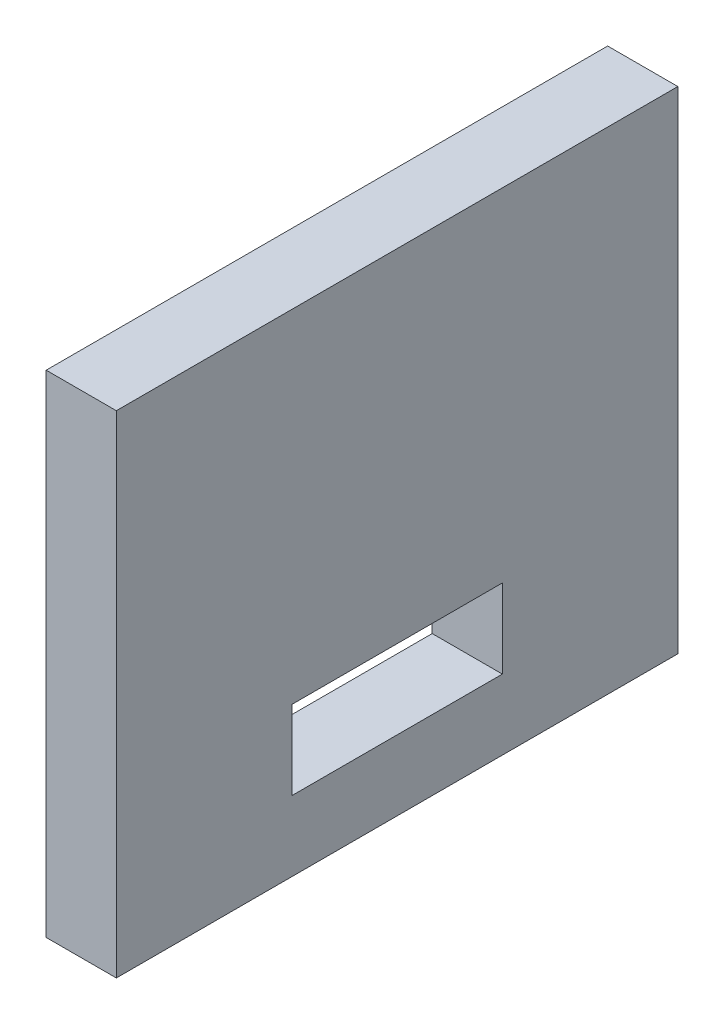
SolidWorks part; units mm, degrees
ref_plane "Front Plane" through (0, 0, 0) normal (0, 0, 1) x (1, 0, 0)
ref_plane "Top Plane" through (0, 0, 0) normal (0, 1, 0) x (1, 0, 0)
ref_plane "Right Plane" through (0, 0, 0) normal (1, 0, 0) x (0, 0, -1)
sketch "Sketch1" plane through (0, 0, 0) normal (1, 0, 0) x (0, 0, -1)
  line L0 (12.7, 3.175) -> (12.7, 0) construction
  line L1 (0, 0) -> (25.4, 0)
  line L2 (0, 0) -> (0, 22.225)
  line L3 (0, 22.225) -> (25.4, 22.225)
  line L4 (25.4, 0) -> (25.4, 22.225)
  line L5 (7.9375, 6.7469) -> (17.4625, 6.7469)
  line L6 (7.9375, 6.7469) -> (7.9375, 3.175)
  line L7 (7.9375, 3.175) -> (17.4625, 3.175)
  line L8 (17.4625, 6.7469) -> (17.4625, 3.175)
  dimension "D1" = 22.225
  dimension "D2" = 25.4
  dimension "D3" = 9.525
  dimension "D4" = 3.5719
  dimension "D5" = 3.175
extrude "Boss-Extrude1" add sketch "Sketch1" along normal blind 3.175
